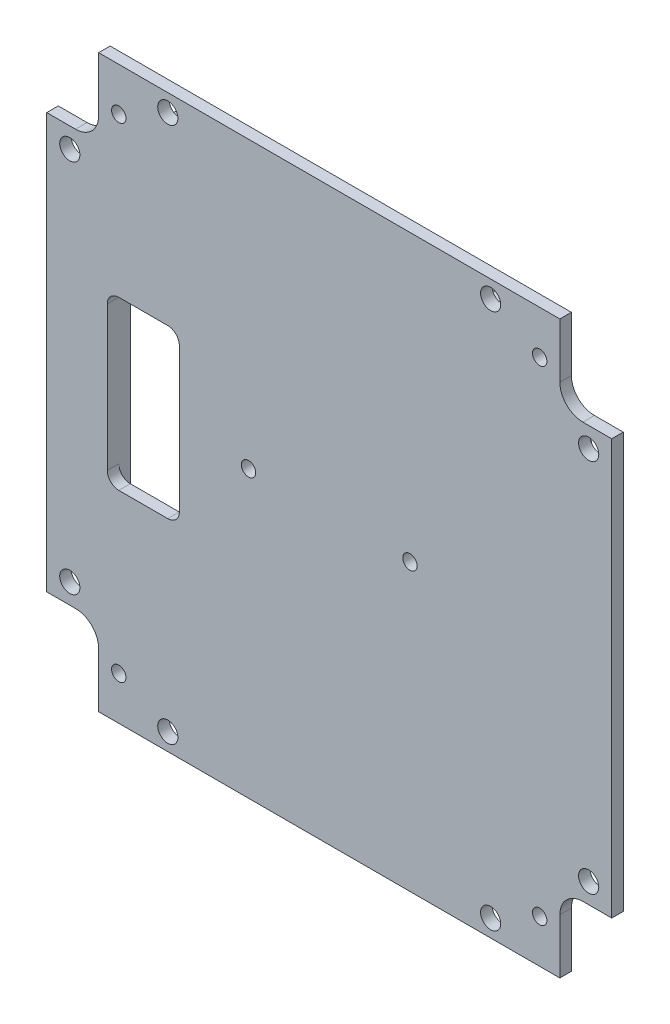
SolidWorks part; units mm, degrees
material "6061-T6 (SS)"
ref_plane "Front Plane" through (0, 0, 0) normal (0, 0, 1) x (1, 0, 0)
ref_plane "Top Plane" through (0, 0, 0) normal (0, 1, 0) x (1, 0, 0)
ref_plane "Right Plane" through (0, 0, 0) normal (1, 0, 0) x (0, 0, -1)
sketch "Sketch1" plane through (0, 0, 0) normal (0, 0, 1) x (1, 0, 0)
  line L1 (0, 0) -> (98, 0)
  line L2 (0, 0) -> (0, 99)
  line L3 (0, 99) -> (98, 99)
  line L4 (98, 0) -> (98, 99)
  dimension "D1" = 98
  dimension "D2" = 99
extrude "Main Body" add sketch "Sketch1" along normal blind 2
sketch "Sketch2" plane through (0, 0, 2) normal (0, 0, 1) x (1, 0, 0)
  line L0 (49, 82) -> (49, 99) construction
  line L1 (4, 82) -> (94, 82) construction
  line L2 (4, 82) -> (4, 17) construction
  line L3 (4, 17) -> (94, 17) construction
  line L4 (94, 82) -> (94, 17) construction
  line L5 (98, 99) -> (0, 99) construction
  line L6 (0, 99) -> (0, 0) construction
  line L7 (94, 49.5) -> (98, 49.5) construction
  line L8 (98, 0) -> (98, 99) construction
  circle A0 centre (4, 82) radius 1.75
  circle A1 centre (94, 82) radius 1.75
  circle A2 centre (94, 17) radius 1.75
  circle A3 centre (4, 17) radius 1.75
  dimension "D3" = 3.5
  dimension "D1" = 4
  dimension "D2" = 65
extrude "FrontBackBoltHoles" cut sketch "Sketch2" against normal through all
sketch "Sketch3" plane through (0, 0, 2) normal (0, 0, 1) x (1, 0, 0)
  line L0 (49, 96) -> (49, 99) construction
  line L1 (21, 96) -> (77, 96) construction
  line L2 (21, 96) -> (21, 3) construction
  line L3 (21, 3) -> (77, 3) construction
  line L4 (77, 96) -> (77, 3) construction
  line L5 (98, 99) -> (0, 99) construction
  line L7 (77, 49.5) -> (98, 49.5) construction
  line L8 (98, 0) -> (98, 99) construction
  circle A0 centre (21, 96) radius 1.75
  circle A1 centre (77, 96) radius 1.75
  circle A2 centre (77, 3) radius 1.75
  circle A3 centre (21, 3) radius 1.75
  dimension "D3" = 3.5
  dimension "D1" = 56
  dimension "D2" = 93
extrude "SideBoltHoles" cut sketch "Sketch3" against normal through all
sketch "Sketch4" plane through (0, 0, 2) normal (0, 0, 1) x (1, 0, 0)
  line L0 (12.5, 49.5) -> (85.5, 49.5) construction
  line L1 (12.5, 91.5) -> (85.5, 91.5) construction
  line L2 (12.5, 91.5) -> (12.5, 7.5) construction
  line L3 (12.5, 7.5) -> (85.5, 7.5) construction
  line L4 (85.5, 91.5) -> (85.5, 7.5) construction
  line L5 (49, 49.5) -> (49, 91.5) construction
  line L6 (12.5, 49.5) -> (0, 49.5) construction
  line L7 (0, 99) -> (0, 0) construction
  line L8 (49, 91.5) -> (49, 99) construction
  line L9 (85.5, 49.5) -> (98, 49.5) construction
  line L10 (98, 0) -> (98, 99) construction
  line L11 (98, 99) -> (0, 99) construction
  line L13 (49, 7.5) -> (49, 0) construction
  line L14 (0, 0) -> (98, 0) construction
  point P8 (35, 49.5)
  point P22 (63, 49.5)
  dimension "D1" = 84
  dimension "D2" = 73
  dimension "D3" = 14
  dimension "D4" = 14
hole_wizard "M3x0.5 Tapped Hole1" positions "Sketch5" profile "Sketch6" tap size "M3x0.5" standard "ANSI Metric"
sketch "Sketch5" plane through (0, 0, 2) normal (0, 0, 1) x (1, 0, 0)
  point P0 (12.5, 91.5)
  point P3 (85.5, 91.5)
  point P6 (85.5, 7.5)
  point P9 (12.5, 7.5)
  point P12 (35, 49.5)
  point P15 (63, 49.5)
sketch "Sketch6" plane through (12.5, 91.5, 2) normal (1, 0, 0) x (0, -1, 0)
  line L0 (0, 0) -> (0, 8.2511)
  line L1 (0, 8.2511) -> (1.25, 7.5)
  line L2 (1.25, 7.5) -> (1.25, 0)
  line L5 (1.25, 0) -> (0, 0)
  line L10 (0, 8.2511) -> (-1.25, 7.5) construction
  line L11 (0, -6.35) -> (0, 107.95) construction
  dimension "Tap Drill Dia." = 2.5
  dimension "Tap Drill Depth" = 7.5
  dimension "Drill Angle" = 118
cosmetic thread "Hole Thread1" parameters "D1"=2, "D2"=3
cosmetic thread "Hole Thread2" parameters "D1"=2, "D2"=3
cosmetic thread "Hole Thread3" parameters "D1"=2, "D2"=3
cosmetic thread "Hole Thread4" parameters "D1"=2, "D2"=3
cosmetic thread "Hole Thread5" parameters "D1"=2, "D2"=3
cosmetic thread "Hole Thread6" parameters "D1"=2, "D2"=3
sketch "Sketch7" plane through (0, 0, 2) normal (0, 0, 1) x (1, 0, 0)
  line L0 (0, 49.5) -> (9, 49.5) construction
  line L1 (9, 85.5) -> (89, 85.5) construction
  line L2 (9, 85.5) -> (9, 13.5) construction
  line L3 (9, 13.5) -> (89, 13.5) construction
  line L4 (89, 85.5) -> (89, 13.5) construction
  line L5 (0, 99) -> (0, 0) construction
  line L7 (49, 85.5) -> (49, 99) construction
  line L8 (98, 99) -> (0, 99) construction
  line L9 (9, 85.5) -> (0, 85.5)
  line L10 (9, 85.5) -> (9, 99)
  line L11 (9, 99) -> (0, 99)
  line L12 (0, 85.5) -> (0, 99)
  line L13 (89, 85.5) -> (98, 85.5)
  line L14 (89, 85.5) -> (89, 99)
  line L15 (89, 99) -> (98, 99)
  line L16 (98, 85.5) -> (98, 99)
  line L17 (98, 0) -> (89, 0)
  line L18 (98, 0) -> (98, 13.5)
  line L19 (98, 13.5) -> (89, 13.5)
  line L20 (89, 0) -> (89, 13.5)
  line L21 (0, 0) -> (9, 0)
  line L22 (0, 0) -> (0, 13.5)
  line L23 (0, 13.5) -> (9, 13.5)
  line L24 (9, 0) -> (9, 13.5)
  dimension "D1" = 80
  dimension "D2" = 72
extrude "Cut-Extrude3" cut sketch "Sketch7" against normal through all
fillet "Fillet1" radius 4 4 edges at (89, 85.5, 1) (9, 13.5, 1) (89, 13.5, 1) (9, 85.5, 1)
sketch "Sketch8" plane through (0, 0, 0) normal (0, 0, -1) x (-1, 0, 0)
  line L0 (-79, 90.5) -> (-79, 8.5) construction
  line L1 (-79, 90.5) -> (-19, 90.5)
  line L2 (-79, 90.5) -> (-79, 93.5)
  line L3 (-79, 93.5) -> (-19, 93.5)
  line L4 (-19, 90.5) -> (-19, 93.5)
  line L5 (-79, 8.5) -> (-19, 8.5)
  line L6 (-79, 8.5) -> (-79, 5.5)
  line L7 (-79, 5.5) -> (-19, 5.5)
  line L8 (-19, 8.5) -> (-19, 5.5)
  line L9 (-79, 49.5) -> (-98, 49.5) construction
  line L10 (-98, 13.5) -> (-98, 85.5) construction
  line L11 (-49, 93.5) -> (-49, 99) construction
  line L12 (-89, 99) -> (-9, 99) construction
  line L13 (-19, 90.5) -> (-19, 8.5) construction
  dimension "D1" = 3
  dimension "D2" = 3
  dimension "D3" = 88
  dimension "D4" = 60
extrude "Boss-Extrude2" add sketch "Sketch8" along normal blind 2
sketch "Sketch9" plane through (0, 0, 0) normal (0, 0, -1) x (-1, 0, 0)
  line L0 (-87.5, 79.5) -> (-10.5, 79.5) construction
  line L1 (-90.5, 79.5) -> (-87.5, 79.5)
  line L2 (-90.5, 79.5) -> (-90.5, 19.5)
  line L3 (-90.5, 19.5) -> (-87.5, 19.5)
  line L4 (-87.5, 79.5) -> (-87.5, 19.5)
  line L5 (-10.5, 79.5) -> (-7.5, 79.5)
  line L6 (-10.5, 79.5) -> (-10.5, 19.5)
  line L7 (-10.5, 19.5) -> (-7.5, 19.5)
  line L8 (-7.5, 79.5) -> (-7.5, 19.5)
  line L9 (-49, 79.5) -> (-49, 99) construction
  line L10 (-89, 99) -> (-9, 99) construction
  line L11 (-10.5, 19.5) -> (-87.5, 19.5) construction
  line L12 (-90.5, 49.5) -> (-98, 49.5) construction
  line L13 (-98, 13.5) -> (-98, 85.5) construction
  dimension "D1" = 83
  dimension "D2" = 3
  dimension "D3" = 3
  dimension "D4" = 60
extrude "Boss-Extrude3" add sketch "Sketch9" along normal blind 2
sketch "Sketch11" plane through (0, 0, 0) normal (0, 0, -1) x (-1, 0, 0)
  line L0 (-12.5, 62) -> (-12.5, 37) construction
  line L1 (-10.5, 62) -> (-10.5, 37)
  line L2 (-14.5, 62) -> (-14.5, 37)
  line L3 (-21, 62) -> (-21, 37) construction
  line L4 (-19, 62) -> (-19, 37)
  line L5 (-23, 62) -> (-23, 37)
  line L6 (-12.5, 62) -> (-21, 62) construction
  line L7 (-10.5, 79.5) -> (-10.5, 19.5) construction
  line L8 (-12.5, 37) -> (-21, 37) construction
  line L9 (-10.5, 79.5) -> (-10.5, 19.5) construction
  line L10 (-12.5, 64) -> (-21, 64)
  line L11 (-21, 62) -> (-21, 64) construction
  line L12 (-12.5, 35) -> (-21, 35)
  arc A0 (-10.5, 62) -> (-14.5, 62) centre (-12.5, 62) ccw
  arc A1 (-14.5, 37) -> (-10.5, 37) centre (-12.5, 37) ccw
  arc A2 (-19, 62) -> (-23, 62) centre (-21, 62) ccw
  arc A3 (-23, 37) -> (-19, 37) centre (-21, 37) ccw
  point P2 (-12.5, 49.5)
  point P7 (-21, 49.5)
  point P20 (-10.5, 49.5)
  point P25 (-10.5, 49.5)
  line M60 (-10.5, 19.5) -> (-10.5, 79.5)
  dimension "D2" = 2
  dimension "D3" = 2
  dimension "D1" = 25
  dimension "D4" = 10.5
extrude "Cut-Extrude5" cut sketch "Sketch11" against normal through all contours L2 A1 A0 M60 | A3 L12 A1 L2 A0 L10 A2 L4 | L5 A3 L4 A2
